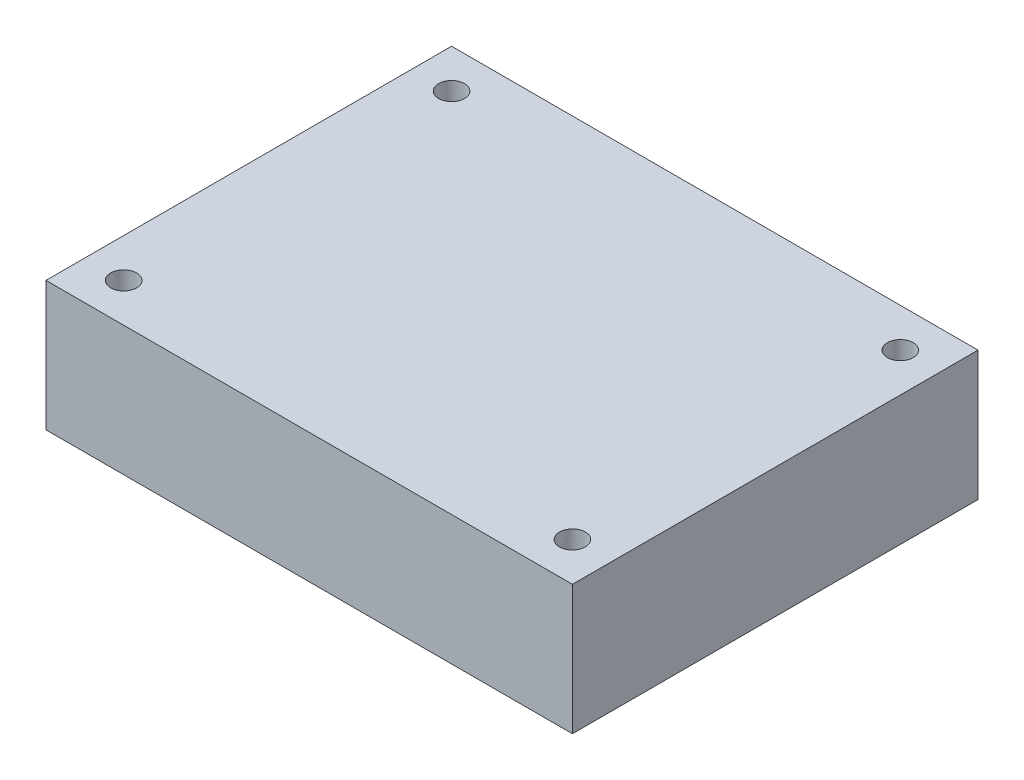
SolidWorks part; units mm, degrees
ref_plane "前视基准面" through (0, 0, 0) normal (0, 0, 1) x (1, 0, 0)
ref_plane "上视基准面" through (0, 0, 0) normal (0, 1, 0) x (1, 0, 0)
ref_plane "右视基准面" through (0, 0, 0) normal (1, 0, 0) x (0, 0, -1)
other "Configuration Table"
sketch "草图1" plane through (0, 0, 0) normal (0, 1, 0) x (1, 0, 0)
  line L0 (0, 47) -> (4.5, 47) construction
  line L1 (0, 0) -> (61, 0)
  line L2 (0, 0) -> (0, 47)
  line L3 (0, 47) -> (61, 47)
  line L4 (61, 0) -> (61, 47)
  line L5 (4.5, 47) -> (4.5, 42.5) construction
  line L6 (61, 47) -> (56.5, 47) construction
  circle A0 centre (4.5, 42.5) radius 1.5
  circle A1 centre (56.5, 42.5) radius 1.5011
  circle A2 centre (4.5, 4.5) radius 1.5
  circle A3 centre (56.5, 4.5) radius 1.5
  dimension "D5" = 3.0022
  dimension "D8" = 3
  dimension "D9" = 3
  dimension "D12" = 3
  dimension "D1" = 4.5
  dimension "D2" = 4.5
  dimension "D3" = 47
  dimension "D4" = 61
  dimension "D6" = 4.5
  dimension "D7" = 4.5
  dimension "D10" = 4.5
  dimension "D11" = 4.5
  dimension "D13" = 4.5
  dimension "D14" = 4.5
extrude "凸台-拉伸2" add sketch "草图1" along normal blind 15
